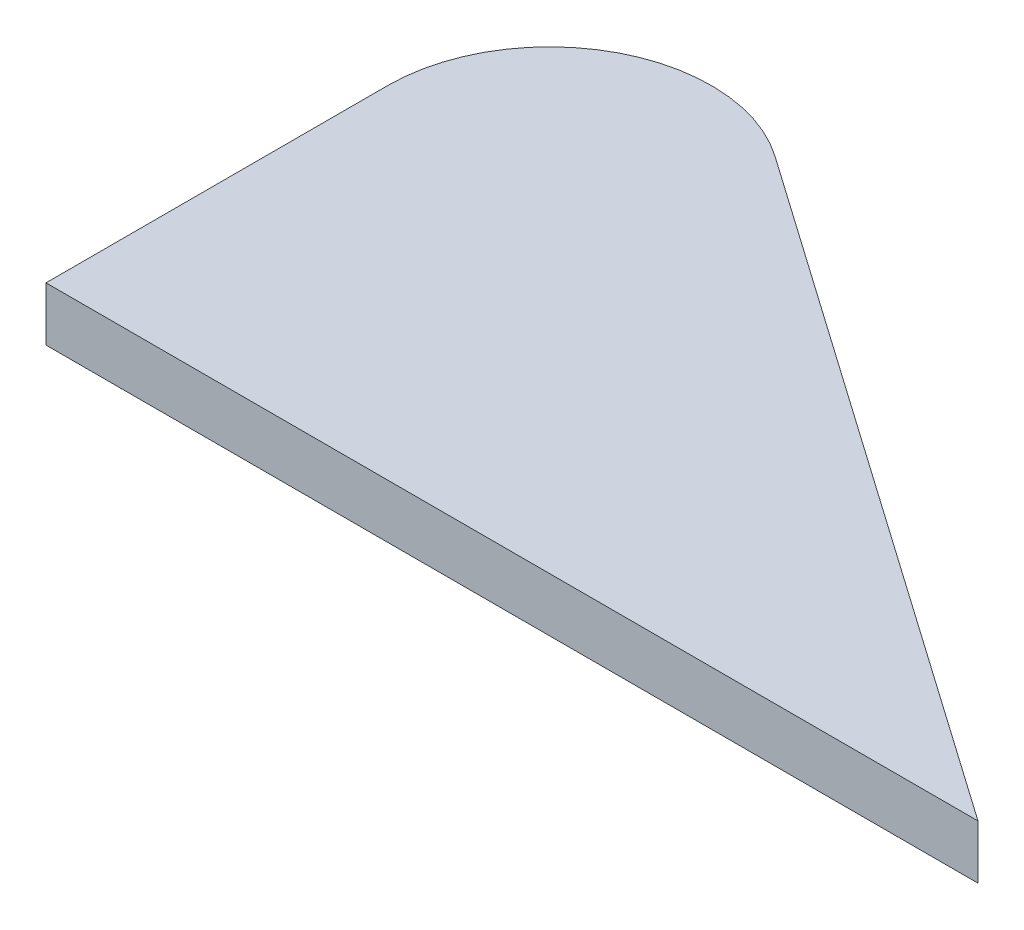
SolidWorks part; units mm, degrees
ref_plane "Front Plane" through (0, 0, 0) normal (0, 0, 1) x (1, 0, 0)
ref_plane "Top Plane" through (0, 0, 0) normal (0, 1, 0) x (1, 0, 0)
ref_plane "Right Plane" through (0, 0, 0) normal (1, 0, 0) x (0, 0, -1)
sketch "Sketch1" plane through (0, 0, 0) normal (0, 1, 0) x (1, 0, 0)
  line L0 (19.05, 63.5) -> (19.05, 0) construction
  line L5 (19.05, 0) -> (109.7374, 0)
  line L6 (109.7374, 0) -> (29.9766, 55.8491)
  line L7 (0, 0) -> (19.05, 0)
  line L8 (8.89, 24.1298) -> (8.89, 8.89)
  line L9 (0, 0) -> (0, 40.2442)
  line L10 (8.89, 8.89) -> (34.29, 8.89)
  line L11 (34.29, 8.89) -> (25.3453, 22.2645)
  line L12 (33.5725, 27.9154) -> (46.99, 8.89)
  line L13 (46.99, 8.89) -> (72.39, 8.89)
  line L14 (72.39, 8.89) -> (36.9441, 33.7095)
  arc A1 (29.9766, 55.8491) -> (0, 40.2442) centre (19.05, 40.2442) ccw
  circle A2 centre (19.05, 40.2442) radius 4.7625
  arc A3 (8.89, 24.1298) -> (25.3453, 22.2645) centre (19.05, 40.2442) ccw
  arc A4 (29.9766, 55.8491) -> (0, 40.2442) centre (19.05, 40.2442) ccw
  arc A5 (33.5725, 27.9154) -> (36.9441, 33.7095) centre (19.05, 40.2442) ccw
  dimension "D3" = 38.1
  dimension "D5" = 9.525
  dimension "D1" = 35
  dimension "D2" = 63.5
  dimension "D4" = 55.8491
  dimension "D6" = 8.89
  dimension "D7" = 8.89
  dimension "D8" = 35
  dimension "D9" = 25.4
  dimension "D10" = 8.89
  dimension "D11" = 12.7
  dimension "D12" = 25.4
extrude "Boss-Extrude2" add sketch "Sketch1" along normal blind 6.35 contours L9 L7 L5 L6 A1
